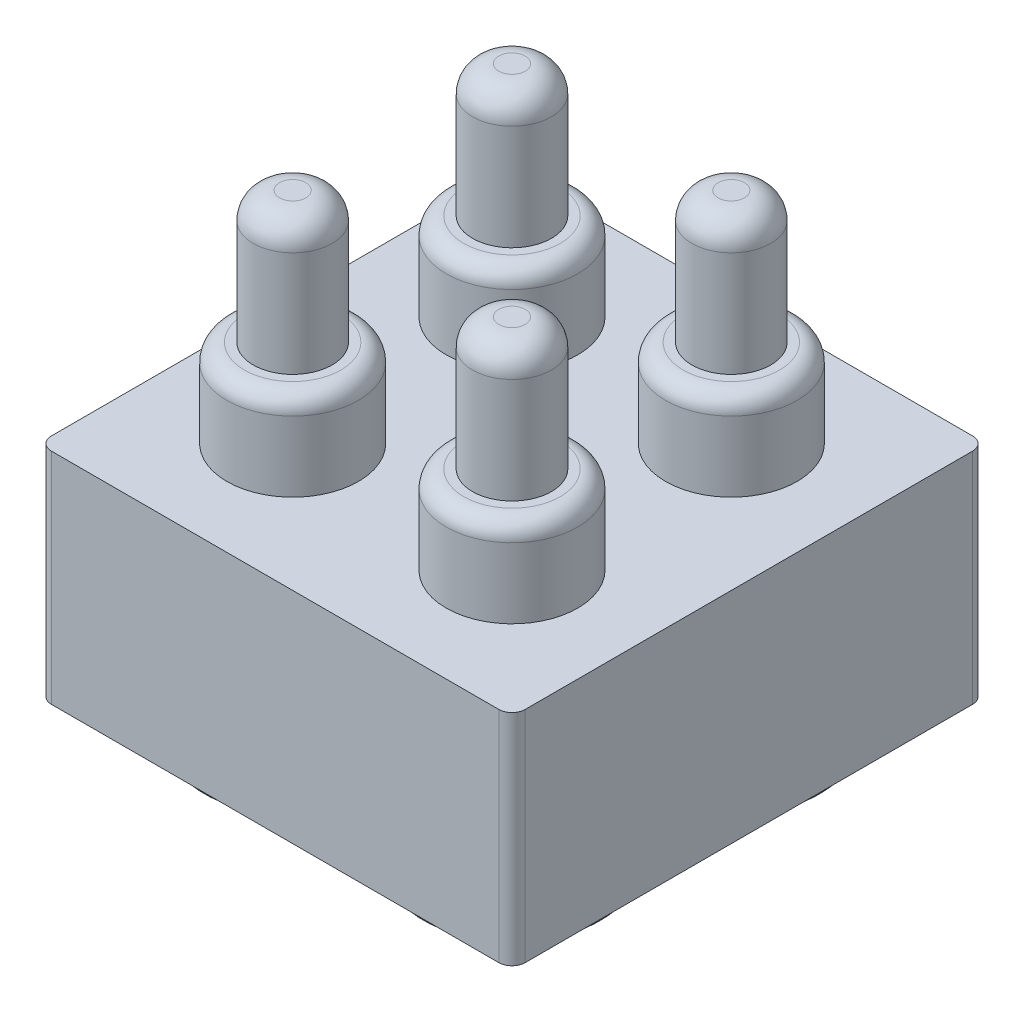
SolidWorks part; units mm, degrees
ref_plane "前视基准面" through (0, 0, 0) normal (0, 0, 1) x (1, 0, 0)
ref_plane "上视基准面" through (0, 0, 0) normal (0, 1, 0) x (1, 0, 0)
ref_plane "右视基准面" through (0, 0, 0) normal (1, 0, 0) x (0, 0, -1)
sketch "草图1" plane through (0, 0, 0) normal (0, 1, 0) x (1, 0, 0)
  line L1 (-2.7, -2.7) -> (2.7, -2.7)
  line L2 (-2.7, -2.7) -> (-2.7, 2.7)
  line L3 (-2.7, 2.7) -> (2.7, 2.7)
  line L4 (2.7, -2.7) -> (2.7, 2.7)
  line L5 (-2.7, -2.7) -> (2.7, 2.7) construction
  line L6 (-2.7, 2.7) -> (2.7, -2.7) construction
  point P0 (0, 0)
  dimension "D1" = 5.4
  dimension "D2" = 5.4
extrude "凸台-拉伸1" add sketch "草图1" along normal blind 2.5
sketch "草图2" plane through (0, 2.5, 0) normal (0, 1, 0) x (1, 0, 0)
  line L0 (-2.7, 2.7) -> (2.7, -2.7) construction
  line L1 (2.7, -2.7) -> (2.6941, -2.7072)
  line L2 (-2.7, 0) -> (2.7, 0) construction
  line L3 (0, 2.7) -> (0, -2.7) construction
  line L4 (2.7, -2.7) -> (2.7, 2.7)
  line L5 (2.7, 2.7) -> (-2.7, 2.7)
  line L6 (-2.7, 2.7) -> (-2.7, -2.7)
  line L7 (-2.7, -2.7) -> (2.7, -2.7)
  line L8 (2.7, -2.7) -> (2.7, 2.7) construction
  line L9 (2.7, 2.7) -> (-2.7, 2.7) construction
  line L10 (-2.7, 2.7) -> (-2.7, -2.7) construction
  line L11 (-2.7, -2.7) -> (2.7, -2.7) construction
  circle A0 centre (-1.25, 1.25) radius 0.75
  circle A1 centre (1.25, 1.25) radius 0.75
  circle A2 centre (-1.25, -1.25) radius 0.75
  circle A3 centre (1.25, -1.25) radius 0.75
  dimension "D3" = 1.5
  dimension "D2" = 2.5
  dimension "D1" = 0
extrude "凸台-拉伸2" add sketch "草图2" along normal blind 1 separate body contours A0 | A1 | A2 | A3
sketch "草图3" plane through (0, 3.5, 0) normal (0, 1, 0) x (1, 0, 0)
  line L0 (-2.7, 0) -> (2.7, 0) construction
  line L1 (0, 2.7) -> (0, -2.7) construction
  line L4 (2.7, -2.7) -> (2.7, 2.7)
  line L5 (2.7, 2.7) -> (-2.7, 2.7)
  line L6 (-2.7, 2.7) -> (-2.7, -2.7)
  line L7 (-2.7, -2.7) -> (2.7, -2.7)
  line L8 (2.7, -2.7) -> (2.7, 2.7) construction
  line L9 (2.7, 2.7) -> (-2.7, 2.7) construction
  line L10 (-2.7, 2.7) -> (-2.7, -2.7) construction
  line L11 (-2.7, -2.7) -> (2.7, -2.7) construction
  circle A0 centre (-1.25, 1.25) radius 0.75 construction
  circle A1 centre (-1.25, 1.25) radius 0.75 construction
  circle A2 centre (-1.25, 1.25) radius 0.45
  circle A3 centre (1.25, 1.25) radius 0.45
  circle A4 centre (1.25, -1.25) radius 0.45
  circle A5 centre (-1.25, -1.25) radius 0.45
  dimension "D2" = 0.9
  dimension "D1" = 0
extrude "凸台-拉伸3" add sketch "草图3" along normal blind 1.5
fillet "圆角2" radius 0.2 1 edges at (-1.25, 3.5, -0.5)
fillet "圆角3" radius 0.2 1 edges at (1.25, 3.5, -0.5)
fillet "圆角4" radius 0.2 1 edges at (1.25, 3.5, 2)
fillet "圆角5" radius 0.2 1 edges at (-1.25, 3.5, 2)
fillet "圆角6" radius 0.3 1 edges at (-1.25, 5, -0.8)
fillet "圆角7" radius 0.3 1 edges at (1.25, 5, -1.7)
fillet "圆角8" radius 0.3 1 edges at (1.25, 5, 1.7)
fillet "圆角9" radius 0.3 1 edges at (-1.25, 5, 0.8)
sketch "草图4" plane through (0, 0, 0) normal (0, -1, 0) x (1, 0, 0)
  circle A0 centre (-1.25, -1.25) radius 0.75 construction
  circle A1 centre (1.25, -1.25) radius 0.75 construction
  circle A2 centre (1.25, 1.25) radius 0.75 construction
  circle A3 centre (-1.25, 1.25) radius 0.75 construction
  circle A4 centre (-1.25, -1.25) radius 0.75 construction
  circle A5 centre (1.25, -1.25) radius 0.75 construction
  circle A6 centre (1.25, 1.25) radius 0.75 construction
  circle A7 centre (-1.25, 1.25) radius 0.75 construction
  circle A8 centre (-1.25, 1.25) radius 1.05
  circle A9 centre (1.25, 1.25) radius 1.05
  circle A10 centre (1.25, -1.25) radius 1.05
  circle A11 centre (-1.25, -1.25) radius 1.05
  dimension "D1" = 2.1
  dimension "D2" = 2.1
  dimension "D3" = 2.1
  dimension "D4" = 2.1
extrude "凸台-拉伸4" add sketch "草图4" along normal blind 0.5 separate body
fillet "圆角10" radius 0.15 1 edges at (-1.25, -0.5, 0.2)
fillet "圆角11" radius 0.15 1 edges at (1.25, -0.5, 0.2)
fillet "圆角12" radius 0.15 1 edges at (-1.25, -0.5, -2.3)
fillet "圆角13" radius 0.15 1 edges at (1.25, -0.5, -2.3)
fillet "圆角14" radius 0.15 4 edges at (-2.7, 1.25, -2.7) (2.7, 1.25, -2.7) (-2.7, 1.25, 2.7) (2.7, 1.25, 2.7)
